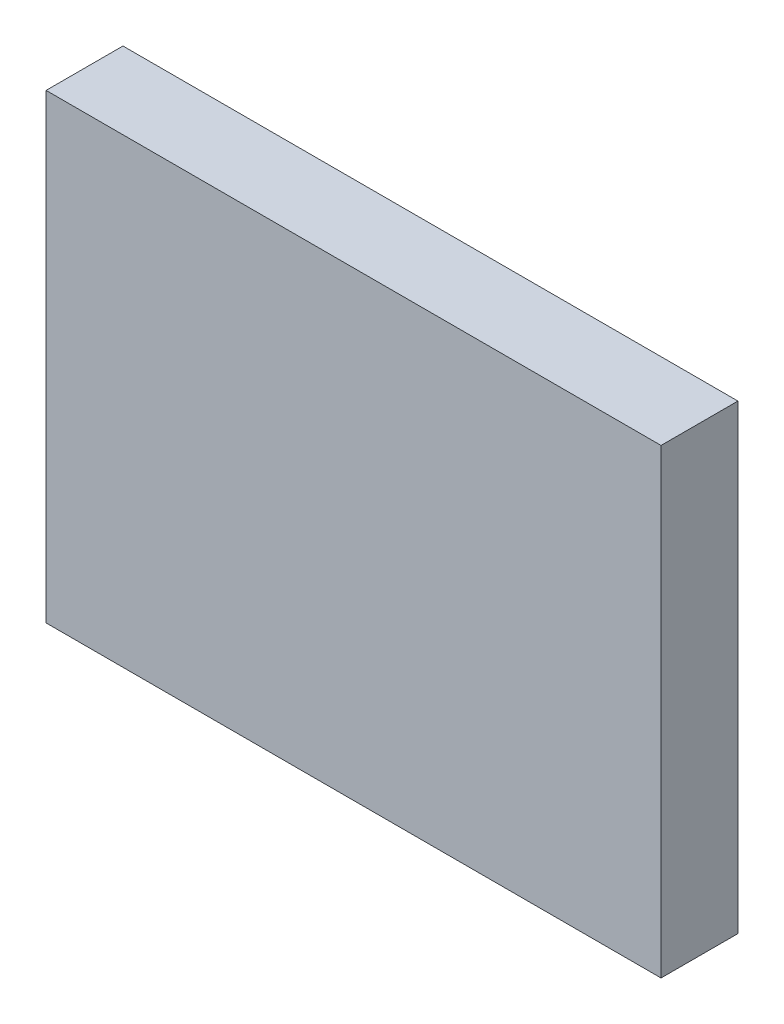
SolidWorks part; units mm, degrees
ref_plane "Front Plane" through (0, 0, 0) normal (1, 0, 0) x (0, 1, 0)
ref_plane "Top Plane" through (0, 0, 0) normal (0, 0, 1) x (0, 1, 0)
ref_plane "Right Plane" through (0, 0, 0) normal (0, 1, 0) x (-1, 0, 0)
sketch "Sketch1" plane through (0, 0, 0) normal (0, 0, 1) x (0, 1, 0)
  line L1 (7.62, -10.16) -> (-7.62, -10.16)
  line L2 (7.62, -10.16) -> (7.62, 10.16)
  line L3 (7.62, 10.16) -> (-7.62, 10.16)
  line L4 (-7.62, -10.16) -> (-7.62, 10.16)
  line L5 (7.62, -10.16) -> (-7.62, 10.16) construction
  line L6 (7.62, 10.16) -> (-7.62, -10.16) construction
  point P0 (0, 0)
  dimension "D1" = 20.32
  dimension "D2" = 15.24
extrude "Boss-Extrude1" add sketch "Sketch1" along normal blind 2.54
